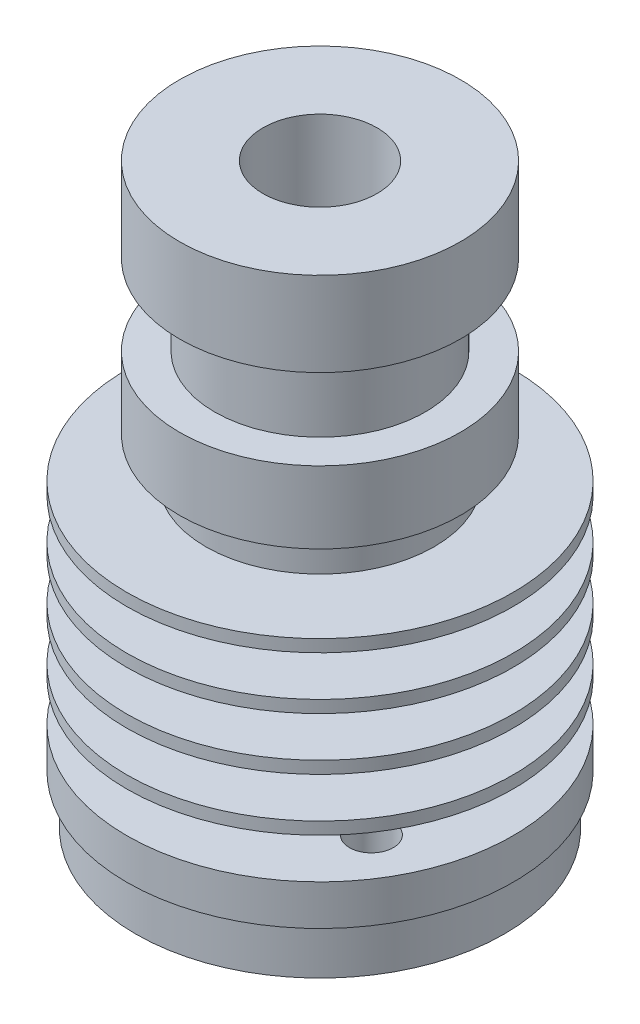
SolidWorks part; units mm, degrees
material "6061-T6 (SS)"
ref_plane "Front Plane" through (0, 0, 0) normal (0, 0, 1) x (1, 0, 0)
ref_plane "Top Plane" through (0, 0, 0) normal (0, 1, 0) x (1, 0, 0)
ref_plane "Right Plane" through (0, 0, 0) normal (1, 0, 0) x (0, 0, -1)
ref_plane "Plane1" through (0, 0, 0) normal (0, 0, -1) x (-1, 0, 0)
sketch "Sketch1" plane through (0, 0, 0) normal (0, 0, -1) x (-1, 0, 0)
  line L0 (-11, 2.8) -> (0, 2.8)
  line L1 (0, 2.8) -> (0, 32.9)
  line L2 (0, 32.9) -> (-8, 32.9)
  line L3 (-8, 32.9) -> (-8, 28.1)
  line L4 (-8, 28.1) -> (-6, 28.1)
  line L5 (-6, 28.1) -> (-6, 23.5)
  line L6 (-6, 23.5) -> (-8, 23.5)
  line L7 (-8, 23.5) -> (-8, 19.4)
  line L8 (-8, 19.4) -> (-6.5, 19.4)
  line L9 (-6.5, 19.4) -> (-6.5, 17.1)
  line L10 (-6.5, 17.1) -> (-11, 17.1)
  line L11 (-11, 17.1) -> (-11, 16.4)
  line L12 (-11, 16.4) -> (-6.5, 16.4)
  line L13 (-6.5, 16.4) -> (-6.5, 14.1)
  line L14 (-6.5, 14.1) -> (-11, 14.1)
  line L15 (-11, 14.1) -> (-11, 13.4)
  line L16 (-11, 13.4) -> (-6.5, 13.4)
  line L17 (-6.5, 13.4) -> (-6.5, 11.1)
  line L18 (-6.5, 11.1) -> (-11, 11.1)
  line L19 (-11, 11.1) -> (-11, 10.4)
  line L20 (-11, 10.4) -> (-6.5, 10.4)
  line L21 (-6.5, 10.4) -> (-6.5, 8.1)
  line L22 (-6.5, 8.1) -> (-11, 8.1)
  line L23 (-11, 8.1) -> (-11, 7.4)
  line L24 (-11, 7.4) -> (-6.5, 7.4)
  line L25 (-6.5, 7.4) -> (-6.5, 5.1)
  line L26 (-6.5, 5.1) -> (-11, 5.1)
  line L27 (-11, 5.1) -> (-11, 2.8)
  line L28 (0, 2.8) -> (0, 32.9) construction
revolve "Revolve1" add sketch "Sketch1" angle 360 about L28
sketch "Sketch2" plane through (0, 2.8, 0) normal (0, -1, 0) x (1, 0, 0)
  circle A0 centre (0, 0) radius 10.5
extrude "Boss-Extrude1" add sketch "Sketch2" along normal blind 2.8
sketch "Sketch3" plane through (0, 0, 0) normal (0, 0, -1) x (-1, 0, 0)
  line L0 (-9.75, 0) -> (0, 0)
  line L1 (0, 0) -> (0, 32.9)
  line L2 (0, 32.9) -> (-3.25, 32.9)
  line L3 (-3.25, 32.9) -> (-3.25, 11.5)
  line L4 (-3.25, 11.5) -> (-4.75, 10)
  line L5 (-4.75, 10) -> (-4.75, 4.55)
  line L6 (-4.75, 4.55) -> (-5.5, 4.55)
  line L7 (-5.5, 4.55) -> (-5.5, 1.55)
  line L8 (-5.5, 1.55) -> (-9.75, 1.55)
  line L9 (-9.75, 1.55) -> (-9.75, 0)
  line L10 (0, 0) -> (0, 32.9) construction
revolve "Cut-Revolve1" cut sketch "Sketch3" angle 360 about L10
hole_wizard "Ø2.5 (2.5) Diameter Hole1" positions "Sketch5" profile "Sketch4" hole size "Ø2.5" standard "ANSI Metric"
sketch "Sketch5" plane through (0, 5.1, 0) normal (0, 1, 0) x (1, 0, 0)
  point P0 (-6.9282, -4)
  point P1 (0, 8)
  point P2 (6.9282, -4)
sketch "Sketch4" plane through (-6.9282, 5.1, 4) normal (1, 0, 0) x (0, 0, 1)
  line L0 (0, 0) -> (0, 5.1)
  line L1 (0, 5.1) -> (1.25, 5.1)
  line L2 (1.25, 5.1) -> (1.25, 0)
  line L5 (1.25, 0) -> (0, 0)
  line L11 (0, -6.35) -> (0, 107.95) construction
  dimension "Thru Hole Dia." = 2.5
  dimension "Thru Hole Depth" = 5.1
chamfer "Chamfer1" distance 0.5 angle 45 2 edges at (-4.75, 4.55, 0) (-5.5, 1.55, 0)
